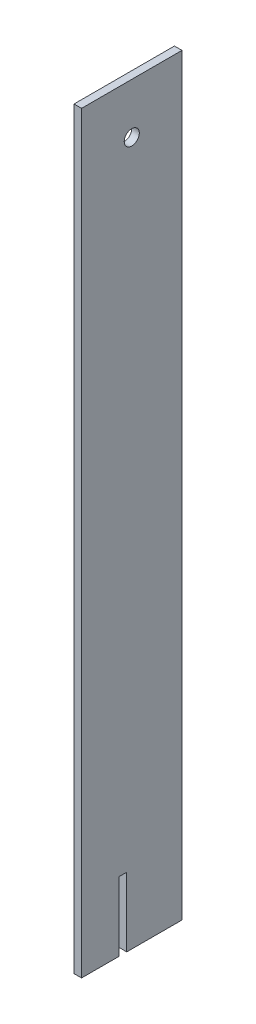
SolidWorks part; units mm, degrees
ref_plane "Front Plane" through (0, 0, 0) normal (0, 0, 1) x (1, 0, 0)
ref_plane "Top Plane" through (0, 0, 0) normal (0, 1, 0) x (1, 0, 0)
ref_plane "Right Plane" through (0, 0, 0) normal (1, 0, 0) x (0, 0, -1)
sketch "Sketch1" plane through (0, 0, 0) normal (1, 0, 0) x (0, 0, -1)
  line L1 (-20, -150) -> (20, -150)
  line L2 (-20, -150) -> (-20, 150)
  line L3 (-20, 150) -> (20, 150)
  line L4 (20, -150) -> (20, 150)
  line L5 (0, 150) -> (0, -150) construction
  line L6 (-20, 0) -> (20, 0) construction
  point P0 (0, 0)
  dimension "D1" = 300
  dimension "D2" = 40
extrude "Boss-Extrude1" add sketch "Sketch1" along normal blind 3
sketch "Sketch2" plane through (3, 0, 0) normal (1, 0, 0) x (0, 0, -1)
  line L0 (-20, 130) -> (20, 130) construction
  line L1 (-20, 150) -> (-20, -150) construction
  line L2 (20, -150) -> (20, 150) construction
  line L3 (20, 150) -> (-20, 150) construction
  circle A0 centre (0, 130) radius 3
  dimension "D1" = 20
extrude "Cut-Extrude1" cut sketch "Sketch2" against normal blind 3
sketch "Sketch3" plane through (3, 0, 0) normal (1, 0, 0) x (0, 0, -1)
  line L0 (-2, -122.5) -> (-2, -150) construction
  line L1 (-20, -150) -> (20, -150) construction
  line L2 (-5, -122.5) -> (-5, -150) construction
  line L4 (-2, -122.5) -> (-5, -122.5)
  line L5 (-2, -122.5) -> (-2, -150)
  line L6 (-2, -150) -> (-5, -150)
  line L7 (-5, -122.5) -> (-5, -150)
extrude "Cut-Extrude2" cut sketch "Sketch3" against normal blind 3
